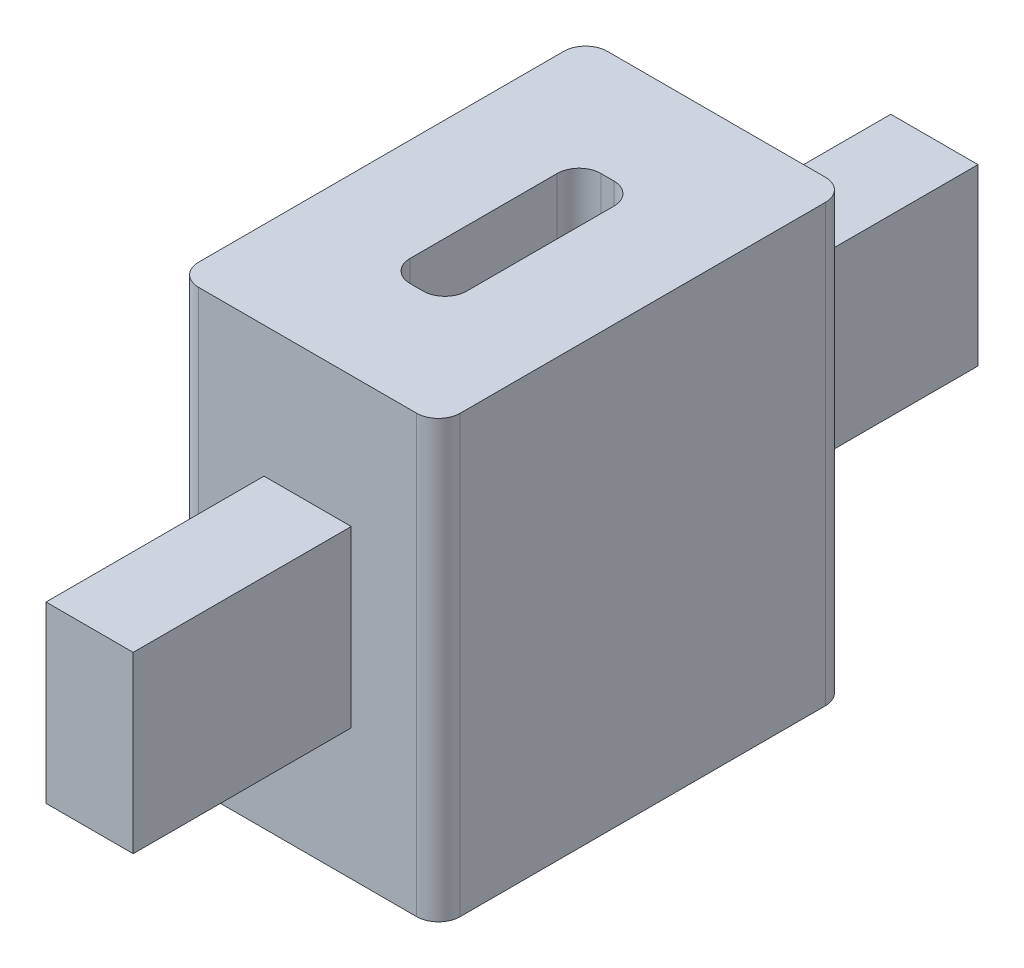
SolidWorks part; units mm, degrees
ref_plane "Front Plane" through (0, 0, 0) normal (0, 0, 1) x (1, 0, 0)
ref_plane "Top Plane" through (0, 0, 0) normal (0, 1, 0) x (1, 0, 0)
ref_plane "Right Plane" through (0, 0, 0) normal (1, 0, 0) x (0, 0, -1)
sketch "Sketch1" plane through (0, 0, 0) normal (0, 1, 0) x (1, 0, 0)
  line L1 (-15.24, -23.8125) -> (15.24, -23.8125)
  line L2 (-15.24, -23.8125) -> (-15.24, 23.8125)
  line L3 (-15.24, 23.8125) -> (15.24, 23.8125)
  line L4 (15.24, -23.8125) -> (15.24, 23.8125)
  line L5 (-15.24, -23.8125) -> (15.24, 23.8125) construction
  line L6 (-15.24, 23.8125) -> (15.24, -23.8125) construction
  point P0 (0, 0)
extrude "Boss-Extrude1" add sketch "Sketch1" along normal blind 50.8
sketch "Sketch2" plane through (0, 50.8, 0) normal (0, 1, 0) x (1, 0, 0)
  line L0 (-15.24, 23.8125) -> (15.24, -23.8125)
  line L4 (-3.302, 0) -> (-3.302, 11.1125)
  line L6 (3.302, 0) -> (3.302, -11.1125)
  line L7 (3.302, -11.1125) -> (-3.302, -11.1125)
  line L8 (-3.302, -11.1125) -> (-3.302, 0)
  line L9 (-3.302, 11.1125) -> (0, 11.1125)
  line L10 (3.302, 0) -> (3.302, 11.1125)
  line L11 (3.302, 11.1125) -> (0, 11.1125)
  line L12 (0, 11.1125) -> (-0.0258, 11.3852)
extrude "Cut-Extrude1" cut sketch "Sketch2" against normal blind 50.8 contours L8 L7 L6 L0 L4 | L10 L11 L9 L4 L0 L6
fillet "Fillet1" radius 2.54 4 edges at (-3.302, 25.4, 11.1125) (3.302, 25.4, -11.1125) (3.302, 25.4, 11.1125) (-3.302, 25.4, -11.1125)
fillet "Fillet2" radius 2.54 4 edges at (15.24, 25.4, 23.8125) (15.24, 25.4, -23.8125) (-15.24, 25.4, 23.8125) (-15.24, 25.4, -23.8125)
sketch "Sketch3" plane through (0, 0, -23.8125) normal (0, 0, -1) x (-1, 0, 0)
  line L0 (-12.7, 0) -> (12.7, 50.8)
  line L2 (5.0806, 15.2388) -> (-5.0806, 15.2388)
  line L3 (5.0806, 15.2388) -> (5.0806, 35.5612)
  line L4 (5.0806, 35.5612) -> (-5.0806, 35.5612)
  line L5 (-5.0806, 15.2388) -> (-5.0806, 35.5612)
  line L6 (5.0806, 15.2388) -> (-5.0806, 35.5612) construction
  line L7 (5.0806, 35.5612) -> (-5.0806, 15.2388) construction
  point P4 (0, 25.4)
  point P9 (-5.0981, 15.2039)
extrude "Boss-Extrude2" add sketch "Sketch3" along normal blind 25.4 contours L5 L0 L4 | L2 L3 L0
sketch "Sketch4" plane through (0, 0, 23.8125) normal (0, 0, 1) x (1, 0, 0)
  line L1 (-5.08, 35.56) -> (5.08, 35.56)
  line L2 (-5.08, 35.56) -> (-5.08, 15.24)
  line L3 (-5.08, 15.24) -> (5.08, 15.24)
  line L4 (5.08, 35.56) -> (5.08, 15.24)
  line L5 (-5.08, 35.56) -> (5.08, 15.24) construction
  line L6 (-5.08, 15.24) -> (5.08, 35.56) construction
  point P0 (0, 25.4)
  point P7 (0, 25.4)
extrude "Boss-Extrude3" add sketch "Sketch4" along normal blind 25.4
